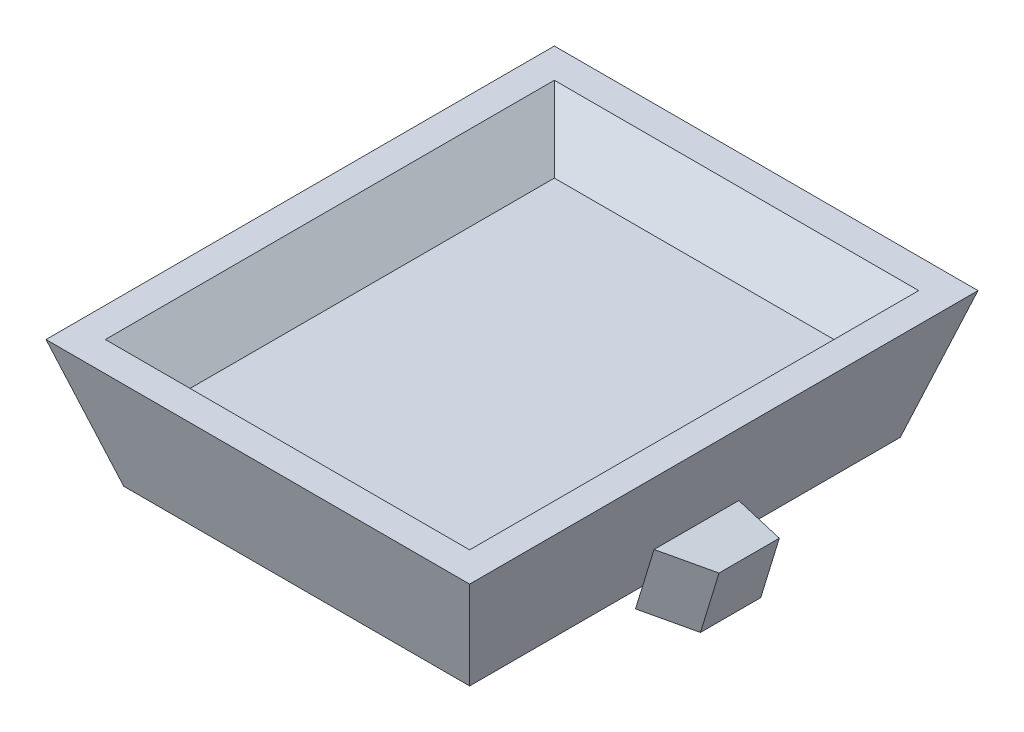
SolidWorks part; units mm, degrees
material "AISI 1020"
ref_plane "Front Plane" through (0, 0, 0) normal (0, 0, 1) x (1, 0, 0)
ref_plane "Top Plane" through (0, 0, 0) normal (0, 1, 0) x (1, 0, 0)
ref_plane "Right Plane" through (0, 0, 0) normal (1, 0, 0) x (0, 0, -1)
sketch "Sketch1" plane through (0, 0, 0) normal (0, 1, 0) x (1, 0, 0)
  line L1 (-50, 60) -> (50, 60)
  line L2 (-50, 60) -> (-50, -60)
  line L3 (-50, -60) -> (50, -60)
  line L4 (50, 60) -> (50, -60)
  line L5 (-50, 60) -> (50, -60) construction
  line L6 (-50, -60) -> (50, 60) construction
  point P0 (0, 0)
  dimension "D1" = 100
  dimension "D2" = 120
extrude "Boss-Extrude1" add sketch "Sketch1" against normal blind 30 draft 17
sketch "Sketch2" plane through (0, 0, 0) normal (0, 1, 0) x (1, 0, 0)
  line L0 (50, 60) -> (-50, 60) construction
  line L1 (-43, -53) -> (43, -53)
  line L2 (-43, -53) -> (-43, 53)
  line L3 (-43, 53) -> (43, 53)
  line L4 (43, -53) -> (43, 53)
  line L5 (-43, -53) -> (43, 53) construction
  line L6 (-43, 53) -> (43, -53) construction
  line L7 (-50, 60) -> (-50, -60) construction
  point P0 (0, 0)
  dimension "D1" = 7
  dimension "D2" = 7
extrude "Cut-Extrude1" cut sketch "Sketch2" against normal blind 10
sketch "Sketch3" plane through (45.7259, -13.9798, 0) normal (0.9563, -0.2924, 0) x (0, 0, -1)
  line L0 (0, 0) -> (0, -15) construction
  line L1 (-10, -22.5) -> (10, -22.5)
  line L2 (-10, -22.5) -> (-10, -7.5)
  line L3 (-10, -7.5) -> (10, -7.5)
  line L4 (10, -22.5) -> (10, -7.5)
  line L5 (-10, -22.5) -> (10, -7.5) construction
  line L6 (-10, -7.5) -> (10, -22.5) construction
  point P0 (0, -15)
  dimension "D1" = 20
  dimension "D2" = 15
  dimension "D3" = 15
extrude "Boss-Extrude2" add sketch "Sketch3" along normal blind 10
draft "Draft1" type of draft neutral plane draft angle 45 faces to draft 4 face at (0, -5, 53) face at (43, -5, 0) face at (0, -5, -53) face at (-43, -5, 0) neutral plane through (0, 0, 0) neutral plane normal (0, 1, 0) parameters "D1"=45
draft "Draft2" type of draft neutral plane draft angle 30 faces to draft 1 face at (45.0631, -29.829, 10) neutral plane through (50, 0, -60) neutral plane normal (0.9563, -0.2924, 0) parameters "D1"=30
